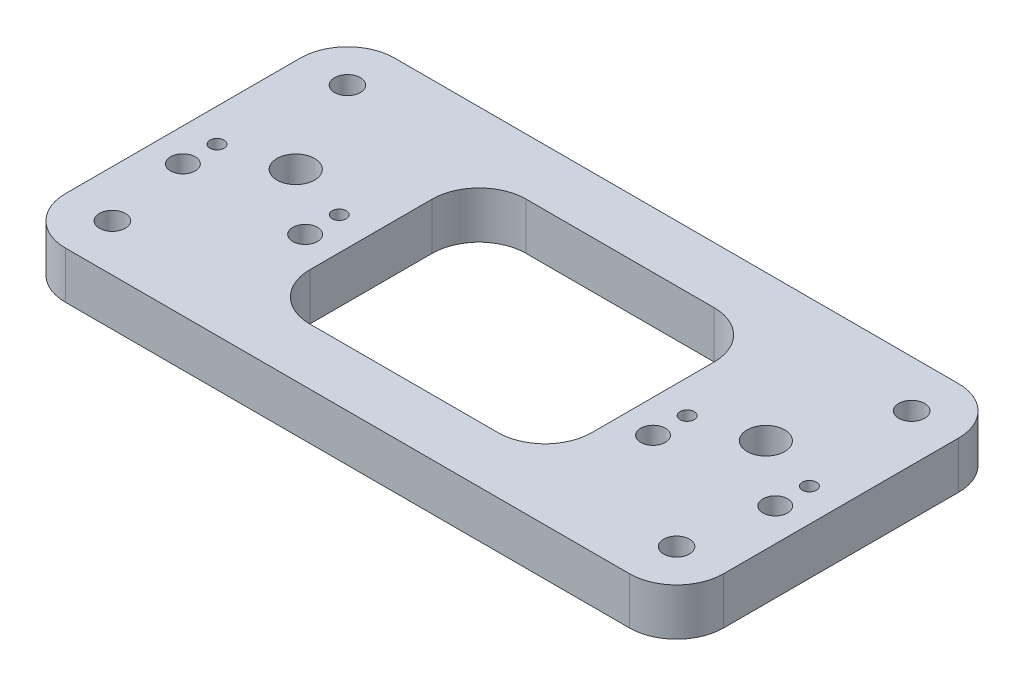
SolidWorks part; units mm, degrees
material "Pine"
ref_plane "Front Plane" through (0, 0, 0) normal (0, 0, 1) x (1, 0, 0)
ref_plane "Top Plane" through (0, 0, 0) normal (0, 1, 0) x (1, 0, 0)
ref_plane "Right Plane" through (0, 0, 0) normal (1, 0, 0) x (0, 0, -1)
sketch "Sketch1" plane through (0, 0, 0) normal (0, 1, 0) x (1, 0, 0)
  line L7 (-70, 35) -> (70, 35)
  line L8 (-70, 35) -> (-70, -35)
  line L9 (-70, -35) -> (70, -35)
  line L10 (70, 35) -> (70, -35)
  line L11 (-70, 35) -> (70, -35) construction
  line L12 (-70, -35) -> (70, 35) construction
  point P0 (0, 0)
  point P6 (0, 0)
  dimension "D3" = 140
  dimension "D4" = 70
extrude "Boss-Extrude1" add sketch "Sketch1" along normal blind 10
fillet "Fillet1" radius 10 4 edges at (70, 5, 35) (70, 5, -35) (-70, 5, -35) (-70, 5, 35)
sketch "Sketch2" plane through (0, 10, 0) normal (0, 1, 0) x (1, 0, 0)
  line L0 (-60, -35) -> (60, -35) construction
  line L1 (-70, 25) -> (-70, -25) construction
  line L2 (0, 0) -> (0, 48.6702) construction
  line L3 (0, 0) -> (23.6821, 0) construction
  circle A0 centre (-60, -25) radius 2.75
  circle A1 centre (-60, 25) radius 2.75
  circle A2 centre (60, -25) radius 2.75
  circle A3 centre (60, 25) radius 2.75
  dimension "D1" = 5.5
  dimension "D2" = 10
  dimension "D3" = 10
extrude "Cut-Extrude1" cut sketch "Sketch2" against normal through all
sketch "Sketch3" plane through (0, 10, 0) normal (0, 1, 0) x (1, 0, 0)
  line L0 (0, 0) -> (0, 59.0273) construction
  line L1 (-70, 25) -> (-70, -25) construction
  line L2 (0, 0) -> (26.0103, 0) construction
  circle A0 centre (-50, 4) radius 4
  circle A1 centre (50, 4) radius 4
  dimension "D1" = 8
  dimension "D2" = 20
  dimension "D3" = 4
extrude "Cut-Extrude2" cut sketch "Sketch3" against normal through all
sketch "Sketch4" plane through (0, 10, 0) normal (0, 1, 0) x (1, 0, 0)
  circle A0 centre (-63, -7) radius 2.625 construction
  circle A1 centre (-63, -7) radius 2.625
  circle A2 centre (-37, -7) radius 2.625 construction
  circle A3 centre (37, -7) radius 2.625 construction
  circle A4 centre (63, -7) radius 2.625 construction
  circle A5 centre (-63, 0.25) radius 1.5 construction
  circle A6 centre (-37, 0.25) radius 1.5 construction
  circle A7 centre (37, 0.25) radius 1.5 construction
  circle A8 centre (63, 0.25) radius 1.5 construction
  circle A9 centre (-37, -7) radius 2.625
  circle A10 centre (37, -7) radius 2.625
  circle A11 centre (63, -7) radius 2.625
  circle A12 centre (-63, 0.25) radius 1.5
  circle A13 centre (-37, 0.25) radius 1.5
  circle A14 centre (37, 0.25) radius 1.5
  circle A15 centre (63, 0.25) radius 1.5
extrude "Cut-Extrude3" cut sketch "Sketch4" against normal through all
sketch "Sketch5" plane through (0, 10, 0) normal (0, 1, 0) x (1, 0, 0)
  line L0 (60, 35) -> (-60, 35) construction
  line L1 (30, 23) -> (-30, 23)
  line L2 (30, 23) -> (30, -23)
  line L3 (30, -23) -> (-30, -23)
  line L4 (-30, 23) -> (-30, -23)
  line L5 (30, 23) -> (-30, -23) construction
  line L6 (30, -23) -> (-30, 23) construction
  line L7 (-30, -7) -> (-30, 4) construction
  point P0 (0, 0)
  dimension "D1" = 12
extrude "Cut-Extrude4" cut sketch "Sketch5" against normal through all
fillet "Fillet3" radius 10 4 edges at (30, 5, -23) (30, 5, 23) (-30, 5, -23) (-30, 5, 23)
